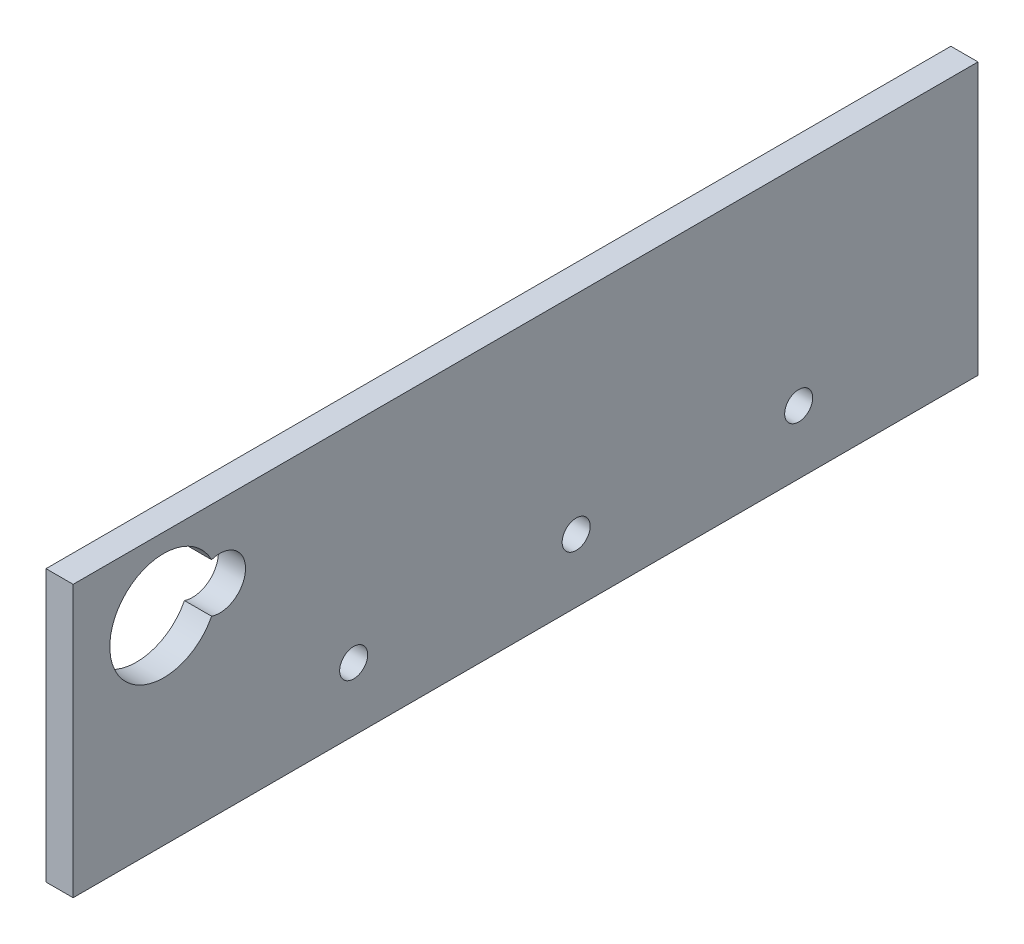
SolidWorks part; units mm, degrees
ref_plane "Ebene vorne" through (0, 0, 0) normal (0, 0, 1) x (1, 0, 0)
ref_plane "Ebene oben" through (0, 0, 0) normal (0, 1, 0) x (1, 0, 0)
ref_plane "Ebene rechts" through (0, 0, 0) normal (1, 0, 0) x (0, 0, -1)
sketch "Skizze1" plane through (0, 0, 0) normal (1, 0, 0) x (0, 0, -1)
  line L1 (0, 0) -> (100, 0)
  line L2 (0, 0) -> (0, 30)
  line L3 (0, 30) -> (100, 30)
  line L4 (100, 0) -> (100, 30)
  dimension "D1" = 100
  dimension "D2" = 30
extrude "Aufsatz-Linear austragen1" add sketch "Skizze1" along normal blind 3
sketch "Skizze2" plane through (3, 0, 0) normal (1, 0, 0) x (0, 0, -1)
  line L0 (10, 0) -> (10, 22) construction
  line L1 (0, 0) -> (100, 0) construction
  line L2 (31, 0) -> (31, 7) construction
  line L3 (55.5919, 0) -> (55.5919, 7) construction
  line L4 (80.1837, 0) -> (80.1837, 7) construction
  line L5 (80.1837, 7) -> (55.5919, 7) construction
  line L6 (55.5919, 7) -> (31, 7) construction
  line L7 (0, 30) -> (0, 0) construction
  circle A0 centre (10, 22) radius 1.55
  circle A1 centre (31, 7) radius 1.55
  circle A2 centre (55.5919, 7) radius 1.55
  circle A3 centre (80.1837, 7) radius 1.55
  dimension "D6" = 3.1
  dimension "D1" = 21
  dimension "D3" = 15
  dimension "D4" = 7
  dimension "D5" = 10
  dimension "D7" = 49.1837
extrude "Bohrungen" cut sketch "Skizze2" against normal through all
sketch "Skizze6" plane through (0, 0, 0) normal (-1, 0, 0) x (0, 0, 1)
  line L0 (-10, 22) -> (0, 22) construction
  line L1 (0, -55) -> (0, 55) construction
  line L2 (-10, 22) -> (-16.2, 22) construction
  arc A0 (-15.3, 19.2958) -> (-15.3, 24.7042) centre (-10, 22) ccw
  arc A1 (-15.3, 24.7042) -> (-15.3, 19.2958) centre (-16.2, 22) ccw
  dimension "D1" = 11.9
  dimension "D2" = 5.7
  dimension "D3" = 6.2
extrude "Schnitt-Linear austragen3" cut sketch "Skizze6" against normal up to surface (3 mm away) up to face at (3, 22, -11.55)
